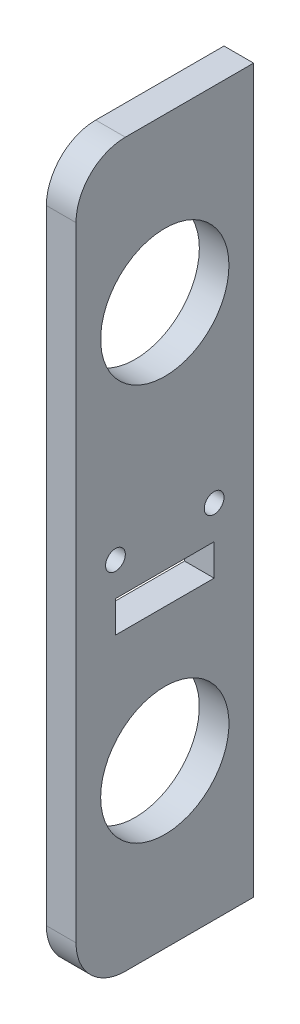
SolidWorks part; units mm, degrees
ref_plane "Alzado" through (0, 0, 0) normal (0, 0, 1) x (1, 0, 0)
ref_plane "Planta" through (0, 0, 0) normal (0, 1, 0) x (1, 0, 0)
ref_plane "Vista lateral" through (0, 0, 0) normal (1, 0, 0) x (0, 0, -1)
sketch "Croquis1" plane through (0, 0, 0) normal (1, 0, 0) x (0, 0, -1)
  line L0 (0, 0) -> (0, 36.6) construction
  line L1 (9, -36.6) -> (-9, -36.6)
  line L2 (9, -36.6) -> (9, 36.6)
  line L3 (9, 36.6) -> (-9, 36.6)
  line L4 (-9, -36.6) -> (-9, 36.6)
  line L5 (9, -36.6) -> (-9, 36.6) construction
  line L6 (9, 36.6) -> (-9, -36.6) construction
  line L7 (0, 0) -> (-9, 0) construction
  line L9 (-5, -6.6) -> (5, -6.6)
  line L10 (-5, -6.6) -> (-5, -3.4)
  line L11 (-5, -3.4) -> (5, -3.4)
  line L12 (5, -6.6) -> (5, -3.4)
  line L13 (-5, -6.6) -> (5, -3.4) construction
  line L14 (-5, -3.4) -> (5, -6.6) construction
  circle A0 centre (0, 20.1) radius 6.5
  circle A1 centre (0, -20.1) radius 6.5
  circle A2 centre (-5, 0) radius 1
  circle A3 centre (5, 0) radius 1
  point P0 (0, 0)
  point P17 (0, -5)
  dimension "D4" = 13
  dimension "D5" = 2
  dimension "D1" = 73.2
  dimension "D2" = 18
  dimension "D3" = 16.5
  dimension "D6" = 4
  dimension "D7" = 40
  dimension "D8" = 10
  dimension "D9" = 3.2
extrude "Saliente-Extruir1" add sketch "Croquis1" along normal blind 3
fillet "Redondeo1" radius 5 2 edges at (1.5, -36.6, 9) (1.5, 36.6, 9)
